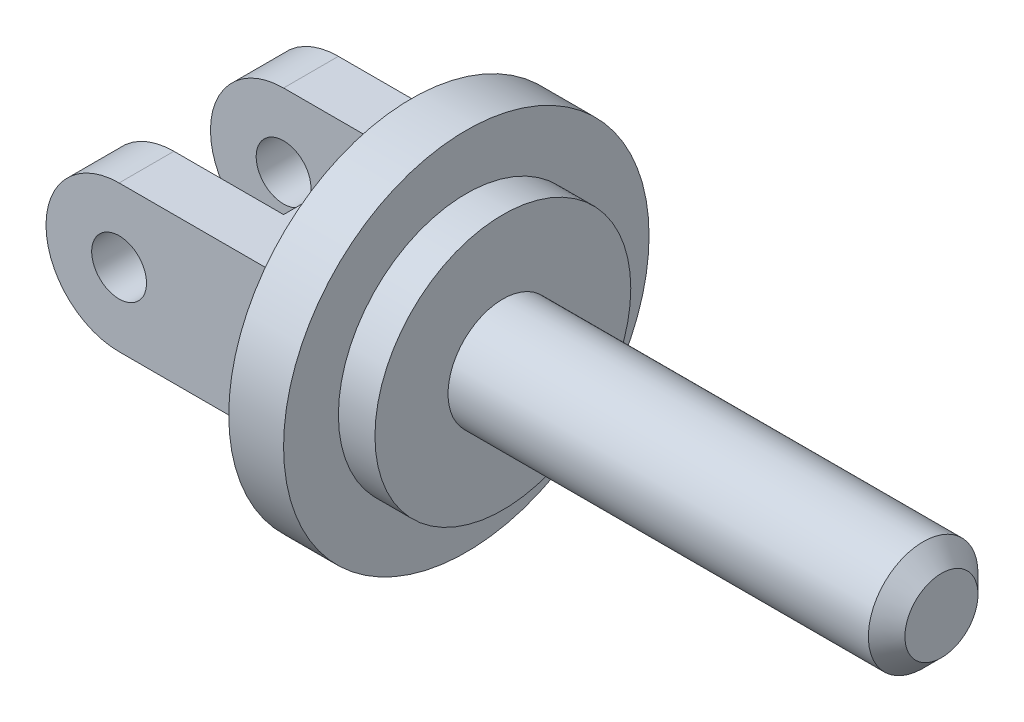
SolidWorks part; units mm, degrees
ref_plane "前视基准面" through (0, 0, 0) normal (0, 0, 1) x (1, 0, 0)
ref_plane "上视基准面" through (0, 0, 0) normal (0, 1, 0) x (1, 0, 0)
ref_plane "右视基准面" through (0, 0, 0) normal (1, 0, 0) x (0, 0, -1)
other "Configuration Table"
sketch "草图1" plane through (0, 0, 0) normal (0, 0, 1) x (1, 0, 0)
  line L0 (0, 2) -> (0, -2) construction
  line L1 (0, 2) -> (5, 2)
  line L2 (0, -2) -> (5, -2)
  line L3 (5, 2) -> (5, -2)
  circle A0 centre (0, 0) radius 2
  circle A1 centre (0, 0) radius 0.75
  dimension "D1" = 4
  dimension "D3" = 1.5
  dimension "D2" = 5
extrude "凸台-拉伸1" add sketch "草图1" along normal mid plane 6 contours A0 L2 L3 L1 | A0 L0 A1 | L0 A0 A1
sketch "草图2" plane through (5, 0, 0) normal (1, 0, 0) x (0, 0, -1)
  circle A0 centre (0, 0) radius 5
  dimension "D1" = 10
extrude "凸台-拉伸2" add sketch "草图2" along normal blind 1.5
sketch "草图3" plane through (6.5, 0, 0) normal (1, 0, 0) x (0, 0, -1)
  circle A0 centre (0, 0) radius 3.5
  dimension "D1" = 7
extrude "凸台-拉伸3" add sketch "草图3" along normal blind 1
sketch "草图4" plane through (7.5, 0, 0) normal (1, 0, 0) x (0, 0, -1)
  circle A1 centre (0, 0) radius 1.5
  dimension "D2" = 3
extrude "凸台-拉伸4" add sketch "草图4" along normal blind 12
sketch "草图5" plane through (0, 2, 0) normal (0, 1, 0) x (1, 0, 0)
  line L0 (-2, 3) -> (-2, -3) construction
  line L1 (-7, -1.5) -> (3, -1.5)
  line L2 (-7, -1.5) -> (-7, 1.5)
  line L3 (-7, 1.5) -> (3, 1.5)
  line L4 (3, -1.5) -> (3, 1.5)
  line L5 (-7, -1.5) -> (3, 1.5) construction
  line L6 (-7, 1.5) -> (3, -1.5) construction
  point P0 (-2, 0)
  dimension "D1" = 3
  dimension "D2" = 10
extrude "切除-拉伸1" cut sketch "草图5" against normal through all
chamfer "倒角1" distance 0.5 angle 45 1 edges at (19.5, 0, -1.5)
